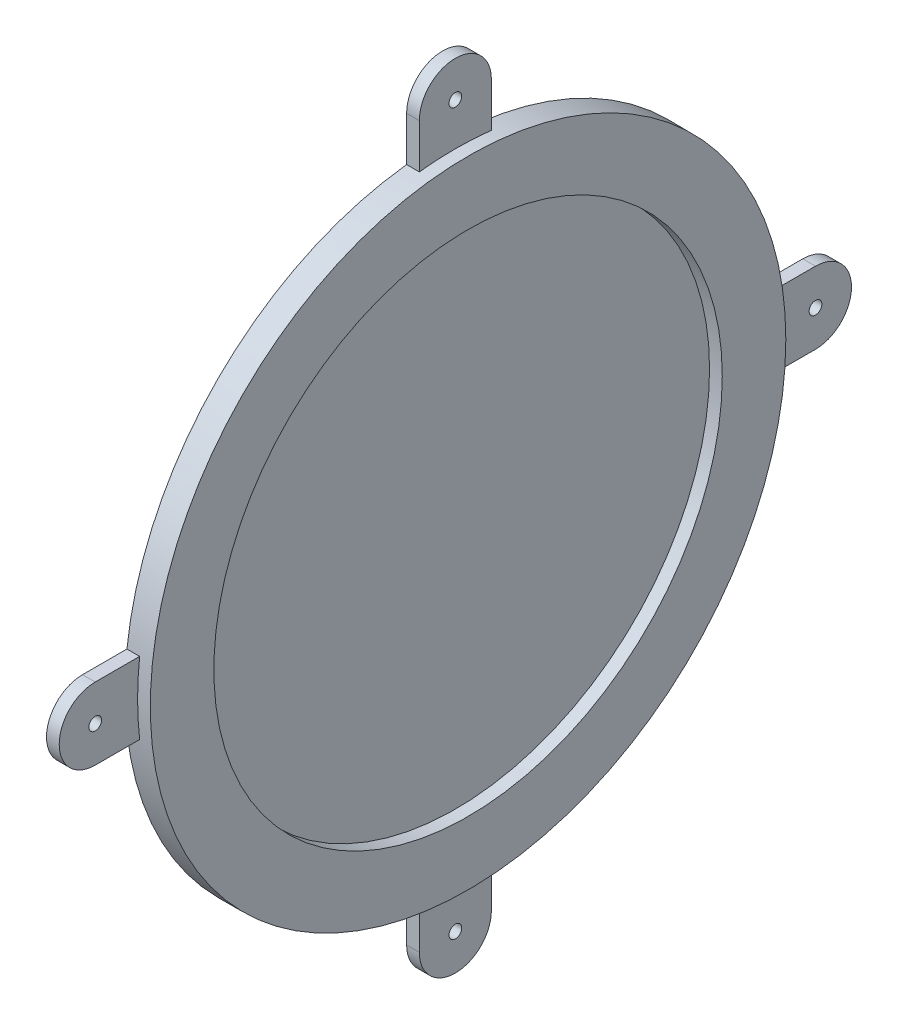
SolidWorks part; units mm, degrees
material "ABS"
ref_plane "Спереди" through (0, 0, 0) normal (0, 0, 1) x (1, 0, 0)
ref_plane "Сверху" through (0, 0, 0) normal (0, 1, 0) x (1, 0, 0)
ref_plane "Справа" through (0, 0, 0) normal (1, 0, 0) x (0, 0, -1)
sketch "Эскиз1" plane through (0, 0, 0) normal (1, 0, 0) x (0, 0, -1)
  line L0 (85, 8.5) -> (74.5168, 8.5)
  line L1 (-8.5, 85) -> (-8.5, 74.5168)
  line L2 (8.5, 85) -> (8.5, 74.5168)
  line L3 (0, 83.5) -> (0, 85)
  line L4 (85, -8.5) -> (74.5168, -8.5)
  line L5 (83.5, 0) -> (85, 0)
  line L6 (8.5, -85) -> (8.5, -74.5168)
  line L7 (-8.5, -85) -> (-8.5, -74.5168)
  line L8 (0, -83.5) -> (0, -85)
  line L9 (-85, -8.5) -> (-74.5168, -8.5)
  line L10 (-85, 8.5) -> (-74.5168, 8.5)
  line L11 (-83.5, 0) -> (-85, 0)
  circle A0 centre (0, 0) radius 75
  circle A1 centre (0, 85) radius 1.5
  arc A2 (8.5, 85) -> (-8.5, 85) centre (0, 85) ccw
  circle A3 centre (85, 0) radius 1.5
  arc A4 (85, -8.5) -> (85, 8.5) centre (85, 0) ccw
  circle A5 centre (0, -85) radius 1.5
  arc A6 (-8.5, -85) -> (8.5, -85) centre (0, -85) ccw
  circle A7 centre (-85, 0) radius 1.5
  arc A8 (-85, 8.5) -> (-85, -8.5) centre (-85, 0) ccw
  point P34 (0, 0)
  dimension "D1" = 4
extrude "Бобышка-Вытянуть1" add sketch "Эскиз1" along normal blind 3 contours A0 | L2 A2 L1 A0 A1 | L4 A4 L0 A0 A3 | L7 A6 L6 A0 A5 | L10 A8 L9 A0 A7
sketch "Эскиз2" plane through (3, 0, 0) normal (1, 0, 0) x (0, 0, -1)
  circle A0 centre (0, 0) radius 75
  circle A1 centre (0, 0) radius 60
extrude "Бобышка-Вытянуть2" add sketch "Эскиз2" along normal blind 3
